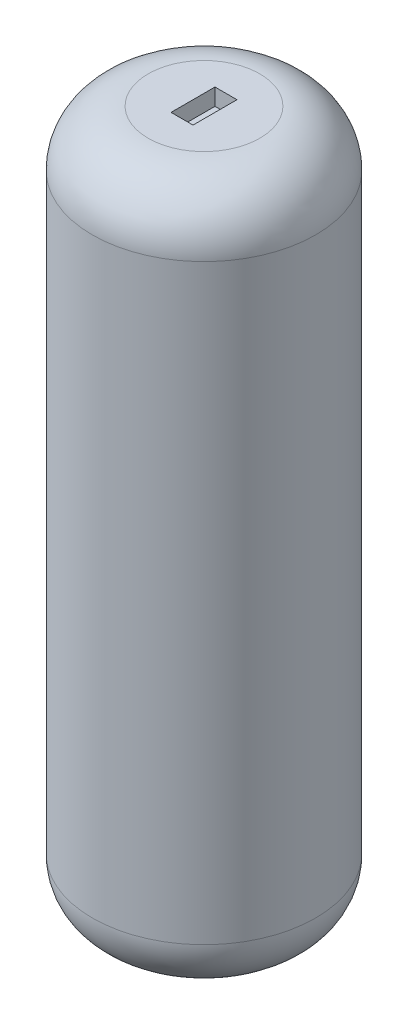
SolidWorks part; units mm, degrees
ref_plane "Front" through (0, 0, 0) normal (0, 0, 1) x (1, 0, 0)
ref_plane "Top" through (0, 0, 0) normal (0, 1, 0) x (1, 0, 0)
ref_plane "Right" through (0, 0, 0) normal (1, 0, 0) x (0, 0, -1)
sketch "Sketch1" plane through (0, 0, 0) normal (0, 1, 0) x (1, 0, 0)
  circle A0 centre (0, 0) radius 50.8
  dimension "D1" = 101.6
extrude "Extrude1" add sketch "Sketch1" along normal blind 320
sketch "Sketch2" plane through (0, 320, 0) normal (0, 1, 0) x (-1, 0, 0)
  circle A0 centre (0, 0) radius 50.8 construction
  point P0 (0, 0)
fillet "Fillet1" radius 25.4 2 edges at (0, 0, 50.8) (0, 320, 50.8)
sketch "Sketch3" plane through (0, 320, 0) normal (0, 1, 0) x (1, 0, 0)
  line L1 (-5, -10) -> (5, -10)
  line L2 (-5, -10) -> (-5, 10)
  line L3 (-5, 10) -> (5, 10)
  line L4 (5, -10) -> (5, 10)
  line L5 (-5, -10) -> (5, 10) construction
  line L6 (-5, 10) -> (5, -10) construction
  point P1 (0, 0)
  dimension "D1" = 10
  dimension "D2" = 20
extrude "Cut-Extrude1" cut sketch "Sketch3" against normal blind 7.62
sketch "Sketch4" plane through (0, 0, 0) normal (0, -1, 0) x (1, 0, 0)
  circle A0 centre (0, 0) radius 19.05
  dimension "D3" = 38.1
extrude "Cut-Extrude2" cut sketch "Sketch4" against normal blind 2.54
